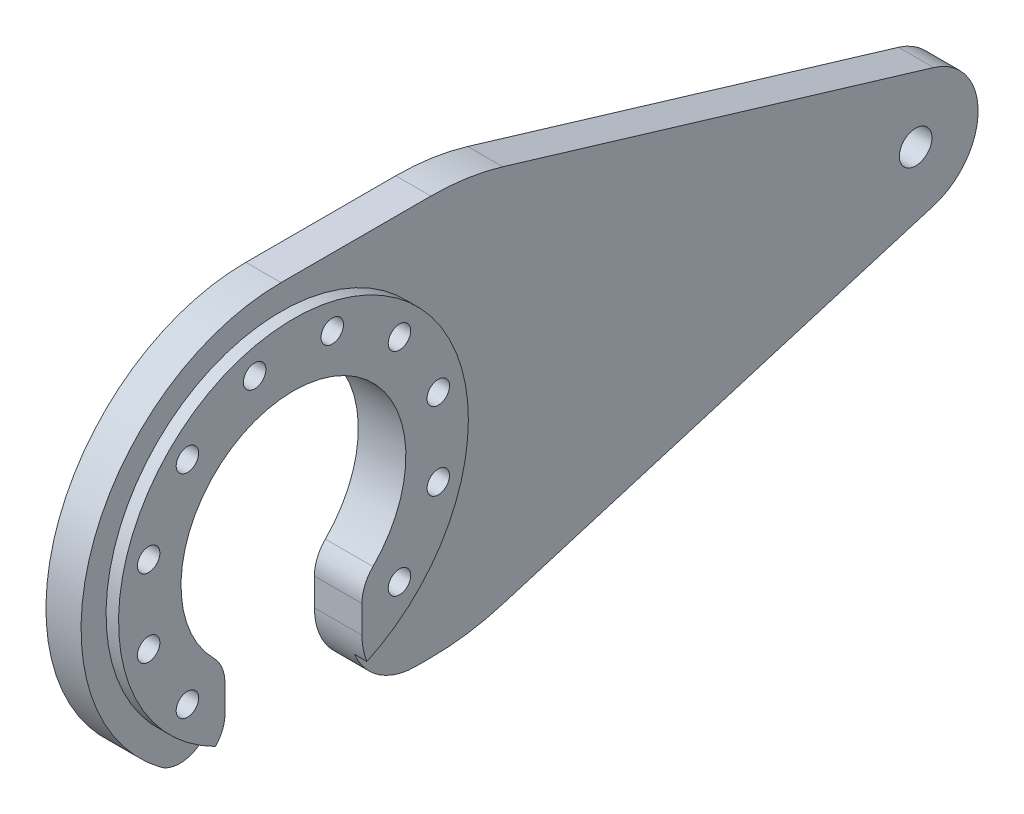
SolidWorks part; units mm, degrees
material "ASTM A36 Steel"
ref_plane "Front Plane" through (0, 0, 0) normal (0, 0, 1) x (1, 0, 0)
ref_plane "Top Plane" through (0, 0, 0) normal (0, 1, 0) x (1, 0, 0)
ref_plane "Right Plane" through (0, 0, 0) normal (1, 0, 0) x (0, 0, -1)
sketch "Sketch1" plane through (0, 0, 0) normal (-1, 0, 0) x (0, 0, 1)
  circle A0 centre (0, 0) radius 22.5
  circle A1 centre (0, 0) radius 35
  circle A2 centre (21.2132, -21.2132) radius 2.25 construction
  circle A3 centre (28.9778, -7.7646) radius 2.25 construction
  circle A4 centre (28.9778, 7.7646) radius 2.25 construction
  circle A5 centre (21.2132, 21.2132) radius 2.25 construction
  circle A6 centre (7.7646, 28.9778) radius 2.25 construction
  circle A7 centre (-7.7646, 28.9778) radius 2.25 construction
  circle A8 centre (-21.2132, 21.2132) radius 2.25 construction
  circle A9 centre (-28.9778, 7.7646) radius 2.25 construction
  circle A10 centre (-28.9778, -7.7646) radius 2.25 construction
  circle A11 centre (-21.2132, -21.2132) radius 2.25 construction
  circle A12 centre (-21.2132, -21.2132) radius 2.25
  circle A13 centre (-28.9778, -7.7646) radius 2.25
  circle A14 centre (-28.9778, 7.7646) radius 2.25
  circle A15 centre (-21.2132, 21.2132) radius 2.25
  circle A16 centre (-7.7646, 28.9778) radius 2.25
  circle A17 centre (7.7646, 28.9778) radius 2.25
  circle A18 centre (21.2132, 21.2132) radius 2.25
  circle A19 centre (28.9778, 7.7646) radius 2.25
  circle A20 centre (28.9778, -7.7646) radius 2.25
  circle A21 centre (21.2132, -21.2132) radius 2.25
  dimension "D1" = 45
  dimension "D2" = 70
extrude "Boss-Extrude1" add sketch "Sketch1" along normal blind 2.5
sketch "Sketch2" plane through (-2.5, 0, 0) normal (-1, 0, 0) x (0, 0, 1)
  line L0 (0, 40) -> (-30, 40)
  line L1 (-44.3935, 37.8835) -> (-130.5984, 11.9709)
  line L2 (-130.5984, -11.9709) -> (-44.3935, -37.8835)
  line L3 (-30, -40) -> (0, -40)
  arc A0 (-30, 40) -> (-44.3935, 37.8835) centre (-30, -10) ccw
  circle A1 centre (0, 0) radius 22.5
  circle A2 centre (0, 0) radius 22.5
  circle A3 centre (-21.2132, -21.2132) radius 2.25
  circle A4 centre (-21.2132, -21.2132) radius 2.25
  circle A5 centre (-28.9778, -7.7646) radius 2.25
  circle A6 centre (-28.9778, -7.7646) radius 2.25
  circle A7 centre (-28.9778, 7.7646) radius 2.25
  circle A8 centre (-28.9778, 7.7646) radius 2.25
  circle A9 centre (-21.2132, 21.2132) radius 2.25
  circle A10 centre (-21.2132, 21.2132) radius 2.25
  circle A11 centre (-7.7646, 28.9778) radius 2.25
  circle A12 centre (-7.7646, 28.9778) radius 2.25
  circle A13 centre (7.7646, 28.9778) radius 2.25
  circle A14 centre (7.7646, 28.9778) radius 2.25
  circle A15 centre (21.2132, 21.2132) radius 2.25
  circle A16 centre (21.2132, 21.2132) radius 2.25
  circle A17 centre (28.9778, 7.7646) radius 2.25
  circle A18 centre (28.9778, 7.7646) radius 2.25
  circle A19 centre (28.9778, -7.7646) radius 2.25
  circle A20 centre (28.9778, -7.7646) radius 2.25
  circle A21 centre (21.2132, -21.2132) radius 2.25
  circle A22 centre (21.2132, -21.2132) radius 2.25
  arc A23 (-130.5984, 11.9709) -> (-130.5984, -11.9709) centre (-127, 0) ccw
  arc A24 (-44.3935, -37.8835) -> (-30, -40) centre (-30, 10) ccw
  arc A25 (0, -40) -> (0, 40) centre (0, 0) ccw
  circle A26 centre (-127, 0) radius 3.2639
  dimension "D12" = 40
  dimension "D13" = 12.5
  dimension "D14" = 50
  dimension "D17" = 6.5278
  dimension "D15" = 30
  dimension "D16" = 127
  dimension "D1" = 0
  dimension "D2" = 0
  dimension "D3" = 0
  dimension "D4" = 0
  dimension "D5" = 0
  dimension "D6" = 0
  dimension "D7" = 0
  dimension "D8" = 0
  dimension "D9" = 0
  dimension "D10" = 0
  dimension "D11" = 0
extrude "Boss-Extrude2" add sketch "Sketch2" along normal offset from surface (7.025 mm away) 9.525 up to face at (0, 0, 35)
sketch "Sketch3" plane through (0, 0, 0) normal (1, 0, 0) x (0, 0, -1)
  line L0 (30, -40) -> (0, -40) construction
  line L1 (26.9985, -40) -> (0, -40)
  line L3 (13.7132, -21.2132) -> (13.7132, -26.7147)
  line L4 (-13.7132, -21.2132) -> (-13.7132, -26.7147)
  circle A0 centre (0, 0) radius 22.5 construction
  arc A1 (-15.9099, -15.9099) -> (15.9099, -15.9099) centre (0, 0) ccw
  arc A2 (-15.9099, -15.9099) -> (-13.7132, -21.2132) centre (-21.2132, -21.2132) cw
  arc A4 (13.7132, -21.2132) -> (15.9099, -15.9099) centre (21.2132, -21.2132) cw
  circle A5 centre (-21.2132, -21.2132) radius 2.25 construction
  arc A9 (13.7132, -26.7147) -> (26.9985, -40) centre (26.9985, -26.7147) ccw
  arc A10 (0, 40) -> (0, -40) centre (0, 0) ccw construction
  arc A11 (-24.1352, -31.8982) -> (0, -40) centre (0, 0) ccw
  arc A12 (-13.7132, -26.7147) -> (-24.1352, -31.8982) centre (-20.2132, -26.7147) cw
  dimension "D1" = 6.5
extrude "Cut-Extrude1" cut sketch "Sketch3" against normal through all
sketch "Sketch4" plane through (-9.525, 0, 0) normal (-1, 0, 0) x (0, 0, 1)
  circle A0 centre (-21.2132, -21.2132) radius 5
  circle A1 centre (-28.9778, -7.7646) radius 5
  circle A2 centre (-28.9778, 7.7646) radius 5
  circle A3 centre (-21.2132, 21.2132) radius 5
  circle A4 centre (-7.7646, 28.9778) radius 5
  circle A5 centre (7.7646, 28.9778) radius 5
  circle A6 centre (21.2132, 21.2132) radius 5
  circle A7 centre (28.9778, 7.7646) radius 5
  circle A8 centre (28.9778, -7.7646) radius 5
  circle A9 centre (21.2132, -21.2132) radius 5
  dimension "D1" = 10
extrude "Cut-Extrude2" cut sketch "Sketch4" against normal offset from surface (4.525 mm away) 5 up to face at (0, -10.7013, -0.0328)
